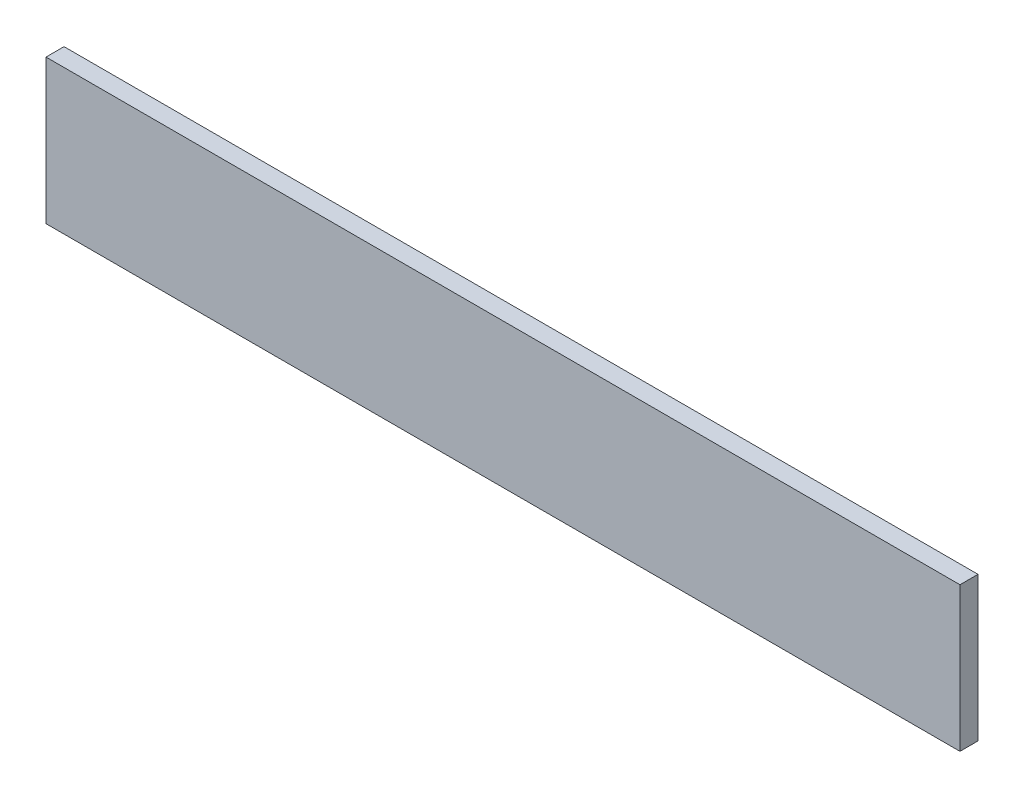
SolidWorks part; units mm, degrees
ref_plane "Front Plane" through (0, 0, 0) normal (0, 0, 1) x (1, 0, 0)
ref_plane "Top Plane" through (0, 0, 0) normal (0, 1, 0) x (1, 0, 0)
ref_plane "Right Plane" through (0, 0, 0) normal (1, 0, 0) x (0, 0, -1)
sketch "Sketch1" plane through (0, 0, 0) normal (0, 0, 1) x (1, 0, 0)
  line L1 (-120.65, -19.05) -> (120.65, -19.05)
  line L2 (-120.65, -19.05) -> (-120.65, 19.05)
  line L3 (-120.65, 19.05) -> (120.65, 19.05)
  line L4 (120.65, -19.05) -> (120.65, 19.05)
  line L5 (0, 19.05) -> (0, -19.05) construction
  line L6 (-120.65, 0) -> (120.65, 0) construction
  point P0 (0, 0)
  dimension "D1" = 38.1
  dimension "D2" = 241.3
extrude "Boss-Extrude1" add sketch "Sketch1" along normal blind 4.7625
